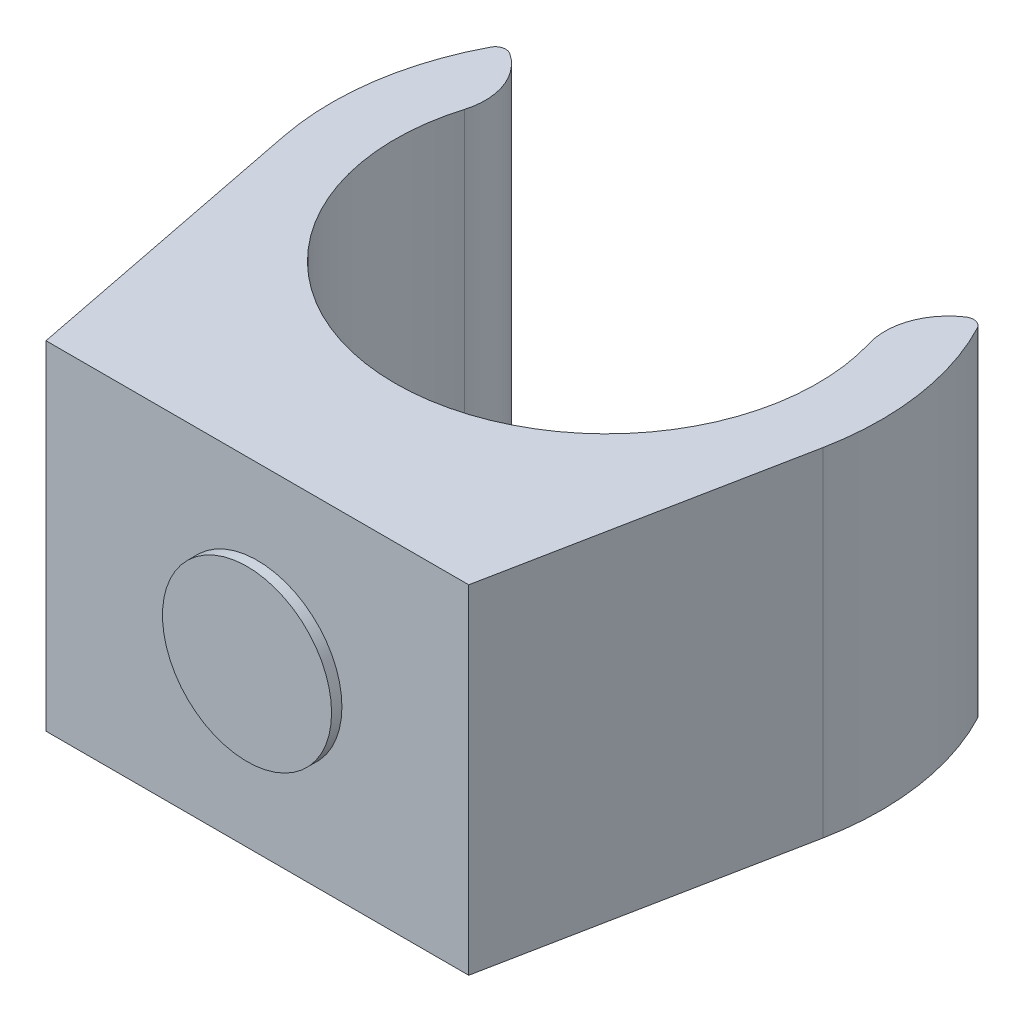
SolidWorks part; units mm, degrees
ref_plane "Alzado" through (0, 0, 0) normal (0, 0, 1) x (1, 0, 0)
ref_plane "Planta" through (0, 0, 0) normal (0, 1, 0) x (1, 0, 0)
ref_plane "Vista lateral" through (0, 0, 0) normal (1, 0, 0) x (0, 0, -1)
sketch "Croquis1" plane through (0, 0, 0) normal (0, 1, 0) x (1, 0, 0)
  line L0 (0, 0) -> (0, 40) construction
  line L1 (0, 0) -> (11.2583, 6.5)
  line L2 (0, 0) -> (-11.2583, 6.5)
  arc A0 (-11.2583, 6.5) -> (11.2583, 6.5) centre (0, 0) ccw
  arc A1 (-8.6603, 5) -> (8.6603, 5) centre (0, 0) ccw
  circle A3 centre (0, 0) radius 10 construction
  circle A4 centre (0, 0) radius 13 construction
  point P3 (38.2522, 11.6949)
  point P8 (37, 0)
  dimension "D1" = 26
  dimension "D3" = 60
  dimension "D2" = 3
extrude "Extruir1" add sketch "Croquis1" along normal blind 16 contours A1 L2 A0 L1
sketch "Croquis2" plane through (0, 0, 0) normal (0, 0, 1) x (1, 0, 0)
  line L0 (0, 0) -> (0, 16) construction
  line L1 (13, 16) -> (-13, 16) construction
  circle A0 centre (0, 8) radius 4
  dimension "D1" = 8
extrude "Extruir2" add sketch "Croquis2" against normal up to surface (4.6307 mm away) from offset 17
fillet "Redondeo1" radius 3 2 edges at (-8.6603, 8, -5) (8.6603, 8, -5)
fillet "Redondeo2" radius 0.5 2 edges at (11.2583, 8, -6.5) (-11.2583, 8, -6.5)
sketch "Croquis3" plane through (0, 16, 0) normal (0, 1, 0) x (1, 0, 0)
  line L0 (-12.7553, -2.5104) -> (-10, -16.5104)
  line L1 (-10, -16.5104) -> (10, -16.5104)
  line L2 (-12.7553, -2.5104) -> (-9.6798, -2.5104)
  line L3 (0, -16.5104) -> (0, -16) construction
  line L4 (12.7553, -2.5104) -> (10, -16.5104)
  line L5 (12.7553, -2.5104) -> (9.6798, -2.5104)
  arc A0 (-11.5118, 6.0398) -> (11.5118, 6.0398) centre (0, 0) ccw construction
  arc A1 (-9.5803, 2.8665) -> (9.5803, 2.8665) centre (0, 0) ccw construction
  arc A2 (-9.6798, -2.5104) -> (9.6798, -2.5104) centre (0, 0) ccw
  dimension "D1" = 10
  dimension "D2" = 14
extrude "Extruir3" add sketch "Croquis3" against normal up to surface (16 mm away) up to face at (0, 0, 0.1544)
